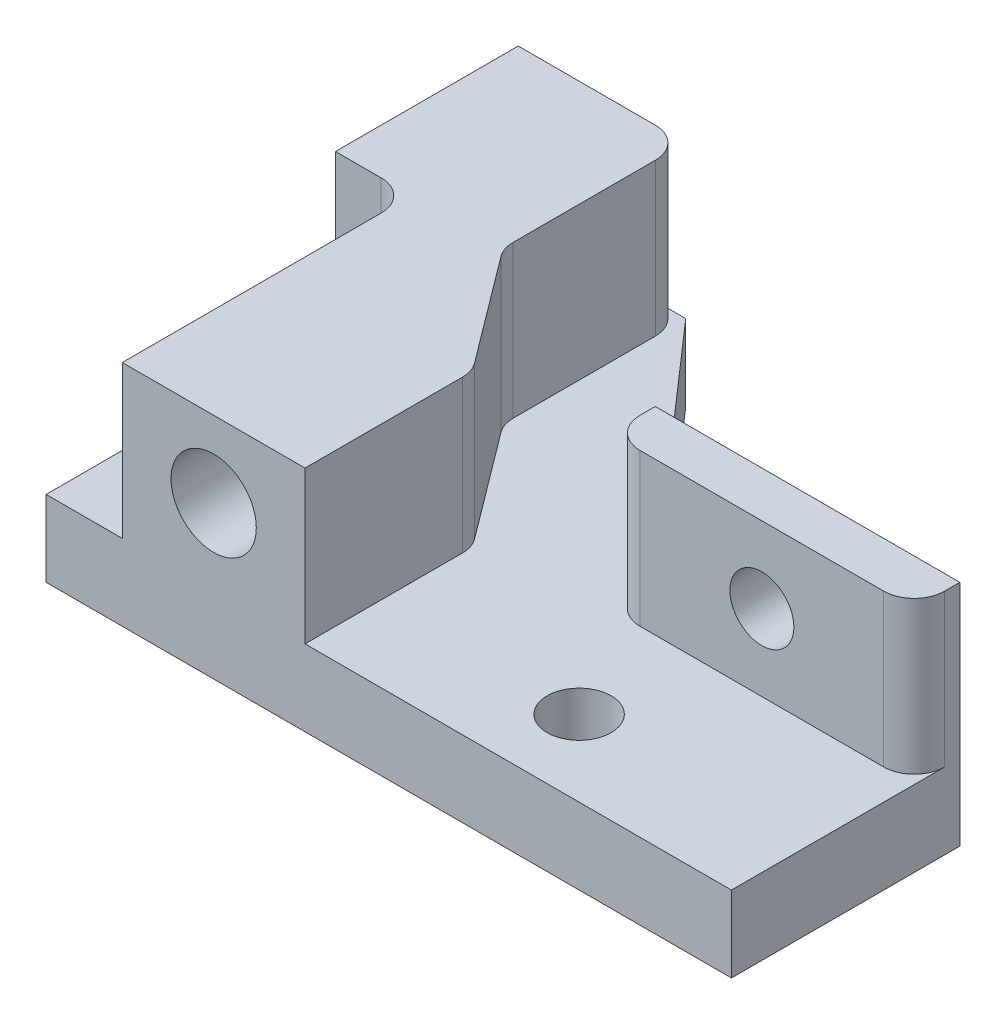
SolidWorks part; units mm, degrees
ref_plane "Plan de face" through (0, 0, 0) normal (0, 0, 1) x (1, 0, 0)
ref_plane "Plan de dessus" through (0, 0, 0) normal (0, 1, 0) x (1, 0, 0)
ref_plane "Plan de droite" through (0, 0, 0) normal (1, 0, 0) x (0, 0, -1)
sketch "Esquisse1" plane through (0, 0, 0) normal (0, 1, 0) x (1, 0, 0)
  line L1 (-72.9133, 0) -> (87.2906, 0) construction
  line L2 (-41.1686, -20) -> (35.315, -20) construction
  line L3 (0, 0) -> (20, 0) construction
  line L4 (0, 0) -> (0, 20) construction
  line L5 (0, 20) -> (20, 20) construction
  line L6 (20, 0) -> (20, 20) construction
  line L7 (20, 0) -> (20, -15)
  line L8 (20, -15) -> (-20, -15)
  line L9 (-20, -15) -> (-20, -4) construction
  line L10 (0, 0) -> (20, 0)
  line L11 (-20, -4) -> (0, 0) construction
  line L14 (-25, 16) -> (-25, -15)
  line L15 (-25, -15) -> (-20, -15)
  line L16 (-25, 16) -> (-14, 16)
  line L17 (-14, 16) -> (0, 0)
  line L18 (-30, 26.004) -> (-30, -86.3557) construction
  line L19 (10, 0) -> (10, -15) construction
  circle A0 centre (5, -10) radius 2.1
  dimension "D6" = 4.2
  dimension "D1" = 20
  dimension "D2" = 20
  dimension "D3" = 5
  dimension "D4" = 11
  dimension "D5" = 40
  dimension "D7" = 31
  dimension "D8" = 11
  dimension "D9" = 5
  dimension "D10" = 40
  dimension "D11" = 5
  dimension "D12" = 10
extrude "Boss.-Extru.1" add sketch "Esquisse1" along normal blind 5
sketch "Esquisse2" plane through (0, 5, 0) normal (0, 1, 0) x (1, 0, 0)
  line L0 (0, 0) -> (0, -3)
  line L1 (0, -3) -> (20, -3)
  line L2 (-20, -4) -> (-8, -4)
  line L3 (-8, -4) -> (-8, -15)
  line L4 (-20, -4) -> (-20, -15)
  line L5 (0, 0) -> (-14, 16)
  line L6 (0, 0) -> (-14, 16)
  line L7 (-25, -15) -> (20, -15)
  line L8 (20, -15) -> (20, 0)
  line L9 (20, 0) -> (0, 0)
  line L12 (-25, -15) -> (20, -15)
  line L13 (20, -15) -> (20, 0)
  line L14 (20, 0) -> (0, 0)
  line L15 (-14, 16) -> (-14, 4)
  line L16 (-14, 4) -> (-25, 4)
  line L17 (-14, -4) -> (-14, -15) construction
  line L18 (10, 0) -> (10, -15) construction
  line L19 (-14, 10) -> (-25, 10) construction
  line L20 (-14, 16) -> (-25, 16)
  line L21 (-14, 16) -> (-25, 16)
  line L22 (-25, 16) -> (-25, -15)
  line L23 (-25, 16) -> (-25, -15)
  line L24 (-20, -4) -> (-20, 4)
  line L25 (-14, 4) -> (-8, -4)
  dimension "D2" = 3
  dimension "D3" = 12
  dimension "D4" = 11
  dimension "D5" = 40
  dimension "D6" = 11
  dimension "D7" = 24
  dimension "D8" = 25
  dimension "D1" = 0
extrude "Boss.-Extru.2" add sketch "Esquisse2" along normal blind 10
sketch "Esquisse3" plane through (0, 0, 15) normal (0, 0, 1) x (1, 0, 0)
  line L0 (-14, 15) -> (-14, 0) construction
  line L1 (-8, 10) -> (-20, 10) construction
  line L2 (-8, 15) -> (-8, 5) construction
  line L3 (-20, 15) -> (-20, 5) construction
  line L4 (-25, 0) -> (20, 0) construction
  line L6 (-25, 0) -> (20, 0)
  line L7 (20, 0) -> (20, 5)
  line L9 (-25, 0) -> (20, 0)
  line L11 (-25, 5) -> (-25, 0)
  line L13 (20, 0) -> (20, 5)
  line L18 (-25, 5) -> (-25, 0)
  line L25 (-8, 15) -> (-20, 15)
  line L27 (-8, 15) -> (-20, 15)
  line L37 (20, 5) -> (-8, 5)
  line L39 (20, 5) -> (-8, 5)
  line L43 (-8, 5) -> (-8, 15)
  line L44 (-8, 5) -> (-8, 15)
  line L45 (-20, 15) -> (-20, 5)
  line L46 (-20, 15) -> (-20, 5)
  line L47 (-20, 5) -> (-25, 5)
  line L48 (-20, 5) -> (-25, 5)
  circle A0 centre (-14, 10) radius 2.8
  dimension "D2" = 5.6
  dimension "D3" = 10
  dimension "D1" = 0
extrude "Enlèv. mat.-Extru.1" cut sketch "Esquisse3" against normal blind 9.1 contours A0
sketch "Esquisse4" plane through (0, 0, 3) normal (0, 0, 1) x (1, 0, 0)
  line L0 (10, 15) -> (10, 5) construction
  line L1 (0, 10) -> (20, 10) construction
  line L4 (0, 5) -> (20, 5)
  line L6 (20, 15) -> (0, 15)
  line L7 (0, 15) -> (0, 5)
  line L10 (20, 15) -> (0, 15)
  line L11 (0, 15) -> (0, 5)
  line L14 (0, 5) -> (20, 5)
  line L18 (20, 5) -> (20, 15)
  line L19 (20, 5) -> (20, 15)
  circle A0 centre (10, 10) radius 2.1
  dimension "D2" = 4.2
  dimension "D1" = 0
extrude "Enlèv. mat.-Extru.2" cut sketch "Esquisse4" against normal blind 9.1 contours A0
fillet "Congé2" radius 2 6 edges at (20, 10, 3) (0, 10, 3) (-20, 10, -4) (-14, 10, -16) (-8, 10, 4) (-14, 10, -4)
sketch "Esquisse5" plane through (-25, 0, 0) normal (-1, 0, 0) x (0, 0, 1)
  line L0 (-10, 15) -> (-10, 0) construction
  line L1 (-4, 10) -> (-16, 10) construction
  line L6 (-16, 0) -> (15, 0)
  line L7 (15, 0) -> (15, 5)
  line L10 (-4, 15) -> (-16, 15)
  line L11 (-16, 15) -> (-16, 0)
  line L12 (-16, 0) -> (15, 0)
  line L13 (15, 0) -> (15, 5)
  line L16 (-4, 15) -> (-16, 15)
  line L17 (-16, 15) -> (-16, 0)
  line L18 (15, 5) -> (-4, 5)
  line L19 (15, 5) -> (-4, 5)
  line L20 (-4, 5) -> (-4, 15)
  line L21 (-4, 5) -> (-4, 15)
  circle A0 centre (-10, 10) radius 2.8
  dimension "D2" = 5.6
  dimension "D1" = 0
extrude "Enlèv. mat.-Extru.3" cut sketch "Esquisse5" against normal blind 9.1 contours A0
